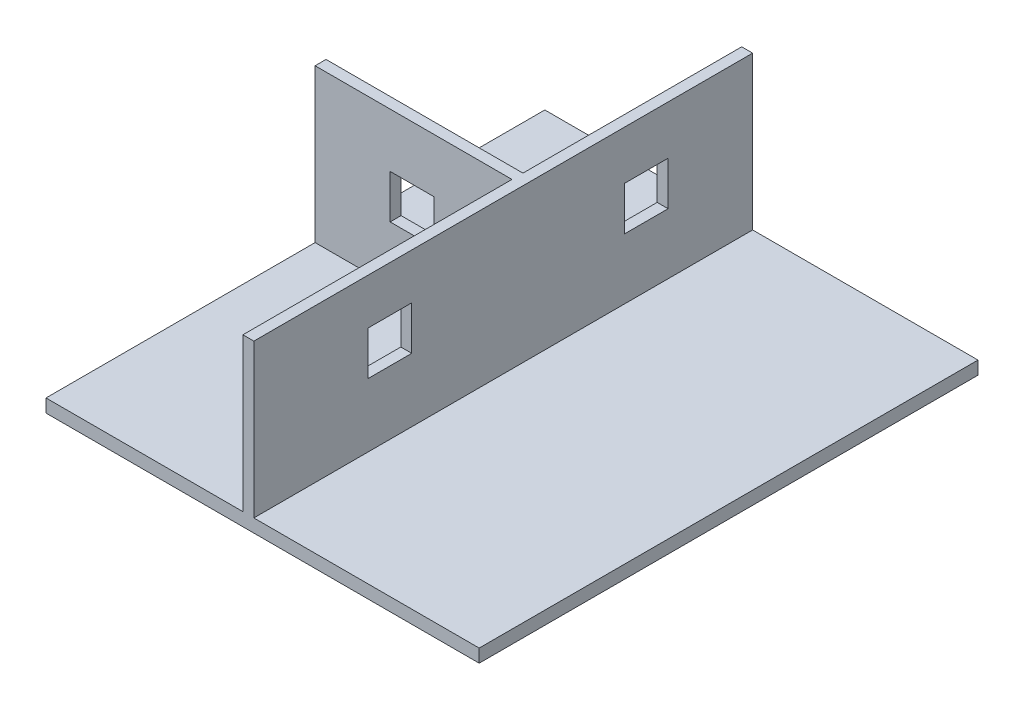
SolidWorks part; units mm, degrees
ref_plane "Front Plane" through (0, 0, 0) normal (0, 0, 1) x (1, 0, 0)
ref_plane "Top Plane" through (0, 0, 0) normal (0, 1, 0) x (1, 0, 0)
ref_plane "Right Plane" through (0, 0, 0) normal (1, 0, 0) x (0, 0, -1)
sketch "Sketch1" plane through (0, 0, 0) normal (0, 1, 0) x (1, 0, 0)
  line L1 (-49.5, 57) -> (49.5, 57)
  line L2 (-49.5, 57) -> (-49.5, -57)
  line L3 (-49.5, -57) -> (49.5, -57)
  line L4 (49.5, 57) -> (49.5, -57)
  line L5 (-49.5, 57) -> (49.5, -57) construction
  line L6 (-49.5, -57) -> (49.5, 57) construction
  point P0 (0, 0)
  dimension "D1" = 114
  dimension "D2" = 99
extrude "Boss-Extrude1" add sketch "Sketch1" along normal blind 3
sketch "Sketch2" plane through (0, 3, 0) normal (0, 1, 0) x (1, 0, 0)
  line L0 (49.5, 57) -> (-49.5, 57) construction
  line L1 (-2, 57) -> (-4.5, 57)
  line L2 (-2, 57) -> (-2, -57)
  line L3 (-2, -57) -> (-4.5, -57)
  line L4 (-4.5, 57) -> (-4.5, 7)
  line L5 (-49.5, -57) -> (49.5, -57) construction
  line L7 (-49.5, 57) -> (-49.5, -57) construction
  line L8 (-4.5, 4.5) -> (-4.5, -57)
  line L9 (-4.5, 7) -> (-49.5, 7)
  line L11 (-4.5, 4.5) -> (-49.5, 4.5)
  line L12 (-49.5, 7) -> (-49.5, 4.5)
  dimension "D1" = 45
  dimension "D2" = 2.5
  dimension "D3" = 2.5
  dimension "D4" = 50
extrude "Boss-Extrude2" add sketch "Sketch2" along normal blind 35
sketch "Sketch3" plane through (0, 0, -4.5) normal (0, 0, 1) x (1, 0, 0)
  line L1 (-32.3521, 25.6633) -> (-22.3521, 25.6633)
  line L2 (-32.3521, 25.6633) -> (-32.3521, 15.6633)
  line L3 (-32.3521, 15.6633) -> (-22.3521, 15.6633)
  line L4 (-22.3521, 25.6633) -> (-22.3521, 15.6633)
  line L5 (-32.3521, 25.6633) -> (-22.3521, 15.6633) construction
  line L6 (-32.3521, 15.6633) -> (-22.3521, 25.6633) construction
  point P0 (-27.3521, 20.6633)
  dimension "D1" = 10
extrude "Cut-Extrude1" cut sketch "Sketch3" against normal blind 35
sketch "Sketch4" plane through (-4.5, 0, 0) normal (-1, 0, 0) x (0, 0, 1)
  line L1 (-37.6785, 26.8633) -> (-27.6785, 26.8633)
  line L2 (-37.6785, 26.8633) -> (-37.6785, 16.8633)
  line L3 (-37.6785, 16.8633) -> (-27.6785, 16.8633)
  line L4 (-27.6785, 26.8633) -> (-27.6785, 16.8633)
  line L5 (-37.6785, 26.8633) -> (-27.6785, 16.8633) construction
  line L6 (-37.6785, 16.8633) -> (-27.6785, 26.8633) construction
  line L7 (20.913, 27.5374) -> (30.913, 27.5374)
  line L8 (20.913, 27.5374) -> (20.913, 17.5374)
  line L9 (20.913, 17.5374) -> (30.913, 17.5374)
  line L10 (30.913, 27.5374) -> (30.913, 17.5374)
  line L11 (20.913, 27.5374) -> (30.913, 17.5374) construction
  line L12 (20.913, 17.5374) -> (30.913, 27.5374) construction
  point P0 (-32.6785, 21.8633)
  point P5 (25.913, 22.5374)
  dimension "D1" = 10
  dimension "D2" = 10
extrude "Cut-Extrude2" cut sketch "Sketch4" against normal blind 35
